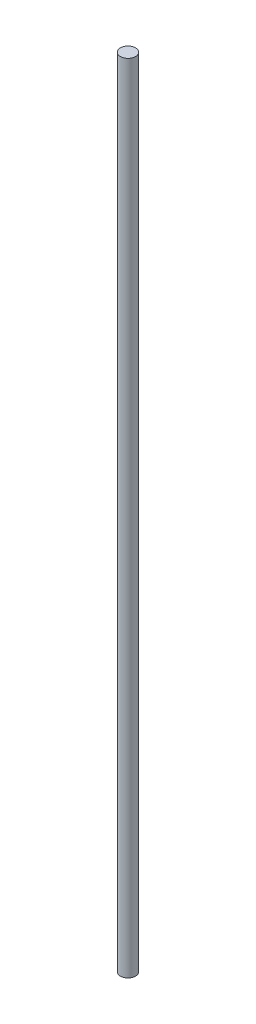
SolidWorks part; units mm, degrees
ref_plane "前视基准面" through (0, 0, 0) normal (0, 0, 1) x (1, 0, 0)
ref_plane "上视基准面" through (0, 0, 0) normal (0, 1, 0) x (1, 0, 0)
ref_plane "右视基准面" through (0, 0, 0) normal (1, 0, 0) x (0, 0, -1)
sketch "草图1" plane through (0, 0, 0) normal (0, 1, 0) x (1, 0, 0)
  circle A0 centre (0, 0) radius 3
  dimension "D1" = 6
extrude "凸台-拉伸1" add sketch "草图1" along normal blind 315
